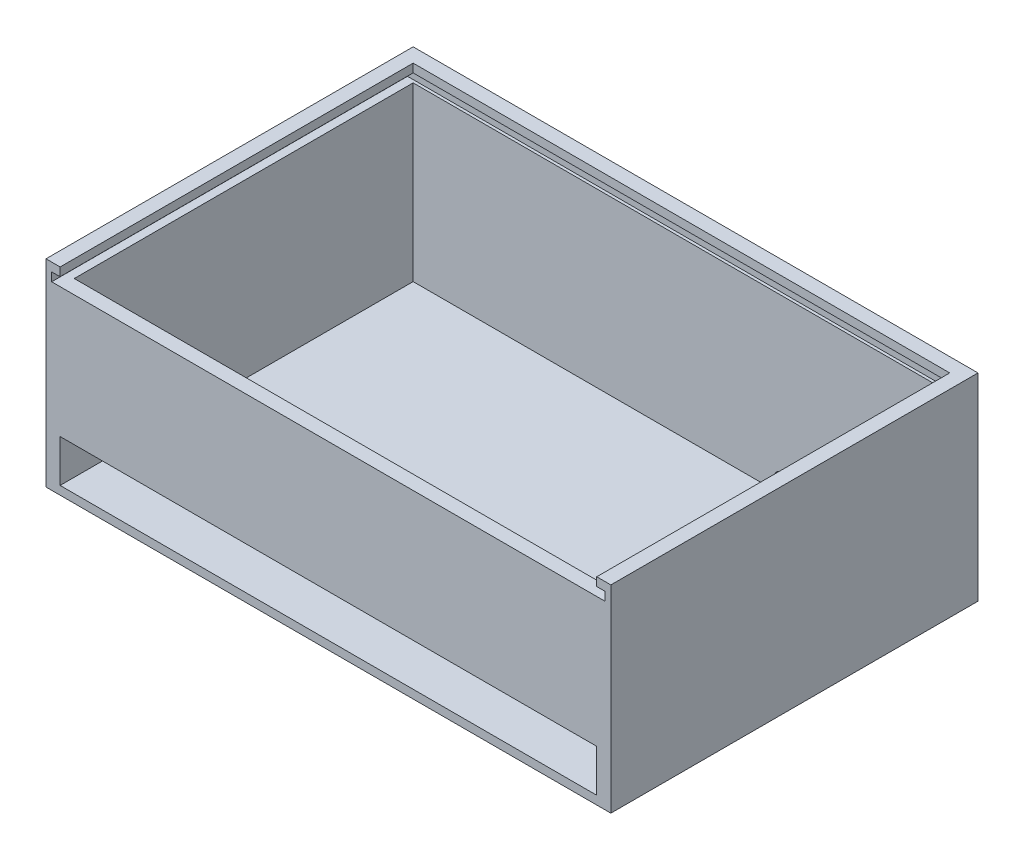
SolidWorks part; units mm, degrees
material "ABS"
ref_plane "Alzado" through (0, 0, 0) normal (0, 0, 1) x (1, 0, 0)
ref_plane "Planta" through (0, 0, 0) normal (0, 1, 0) x (1, 0, 0)
ref_plane "Vista lateral" through (0, 0, 0) normal (1, 0, 0) x (0, 0, -1)
sketch "Croquis1" plane through (0, 0, 0) normal (0, 1, 0) x (1, 0, 0)
  line L1 (-100, 65) -> (100, 65)
  line L2 (-100, 65) -> (-100, -65)
  line L3 (-100, -65) -> (100, -65)
  line L4 (100, 65) -> (100, -65)
  line L5 (-100, 65) -> (100, -65) construction
  line L6 (-100, -65) -> (100, 65) construction
  point P0 (0, 0)
  dimension "D1" = 200
  dimension "D2" = 130
extrude "Saliente-Extruir1" add sketch "Croquis1" along normal blind 3
sketch "Croquis2" plane through (0, 3, 0) normal (0, 1, 0) x (1, 0, 0)
  line L0 (100, -65) -> (100, 65) construction
  line L1 (-100, 65) -> (100, 65)
  line L2 (-100, 65) -> (-100, 60)
  line L3 (-100, 60) -> (100, 60)
  line L4 (100, 65) -> (100, 60)
  line L5 (-100, -65) -> (100, -65) construction
  line L6 (-100, 65) -> (-95, 65)
  line L7 (-100, 65) -> (-100, -65)
  line L8 (-100, -65) -> (-95, -65)
  line L9 (-95, 65) -> (-95, -65)
  line L11 (95, 65) -> (100, 65)
  line L12 (95, 65) -> (95, -65)
  line L13 (95, -65) -> (100, -65)
  line L14 (100, 65) -> (100, -65)
  line L15 (-100, -60) -> (100, -60)
  line L16 (-100, -60) -> (-100, -65)
  line L17 (-100, -65) -> (100, -65)
  line L18 (100, -60) -> (100, -65)
  line M9 (100, -65) -> (100, 65)
  line M10 (100, 65) -> (-100, 65)
  line M11 (-100, 65) -> (-100, -65)
  line M12 (-100, -65) -> (100, -65)
  dimension "D1" = 5
  dimension "D2" = 5
  dimension "D3" = 5
  dimension "D4" = 5
extrude "Saliente-Extruir2" add sketch "Croquis2" along normal blind 67 contours L9 L1 L3 M11 | L15 L9 L3 M11 | L12 L1 L9 L3 | L12 L3 M10 M9 | L15 L7 L9 M12 | L12 L15 L14 L3 | L15 L9 L12 M12 | L15 L12 M12 M9
sketch "Croquis3" plane through (0, 0, 65) normal (0, 0, 1) x (1, 0, 0)
  line L0 (95, 70) -> (95, 3) construction
  line L1 (-95, 3) -> (95, 3)
  line L2 (-95, 3) -> (-95, 18)
  line L3 (-95, 18) -> (95, 18)
  line L4 (95, 3) -> (95, 18)
  dimension "D1" = 15
extrude "Cortar-Extruir1" cut sketch "Croquis3" against normal up to surface (5 mm away) up to face at (0, 36.5, 60)
sketch "Croquis4" plane through (0, 0, 65) normal (0, 0, 1) x (1, 0, 0)
  line L5 (100, 70) -> (100, 0) construction
  line L6 (-98, 67) -> (98, 67)
  line L7 (-98, 67) -> (-98, 63.95)
  line L8 (-98, 63.95) -> (98, 63.95)
  line L9 (98, 67) -> (98, 63.95)
  line L10 (-100, 70) -> (-100, 0) construction
  line L11 (-100, 70) -> (100, 70) construction
  dimension "D1" = 3
  dimension "D2" = 2
  dimension "D3" = 2
  dimension "D4" = 3.05
extrude "Cortar-Extruir2" cut sketch "Croquis4" against normal blind 126
sketch "Croquis7" plane through (0, 0, 60) normal (0, 0, -1) x (-1, 0, 0)
  line L1 (-95, 70) -> (95, 70)
  line L2 (-95, 70) -> (-95, 67)
  line L3 (-95, 67) -> (95, 67)
  line L4 (95, 70) -> (95, 67)
extrude "Cortar-Extruir3" cut sketch "Croquis7" against normal up to surface (5 mm away) up to face at (0, 65.475, 65)
sketch "Croquis8" plane through (0, 0, -65) normal (0, 0, -1) x (-1, 0, 0)
  line L0 (-100, 70) -> (-100, 0) construction
  line L1 (-100, 0) -> (100, 0) construction
  circle A0 centre (-35, 7.5) radius 2
  dimension "D1" = 4
  dimension "D2" = 65
  dimension "D3" = 7.5
extrude "Cortar-Extruir4" cut sketch "Croquis8" against normal up to surface (5 mm away) up to face at (0, 68.5, -60)
